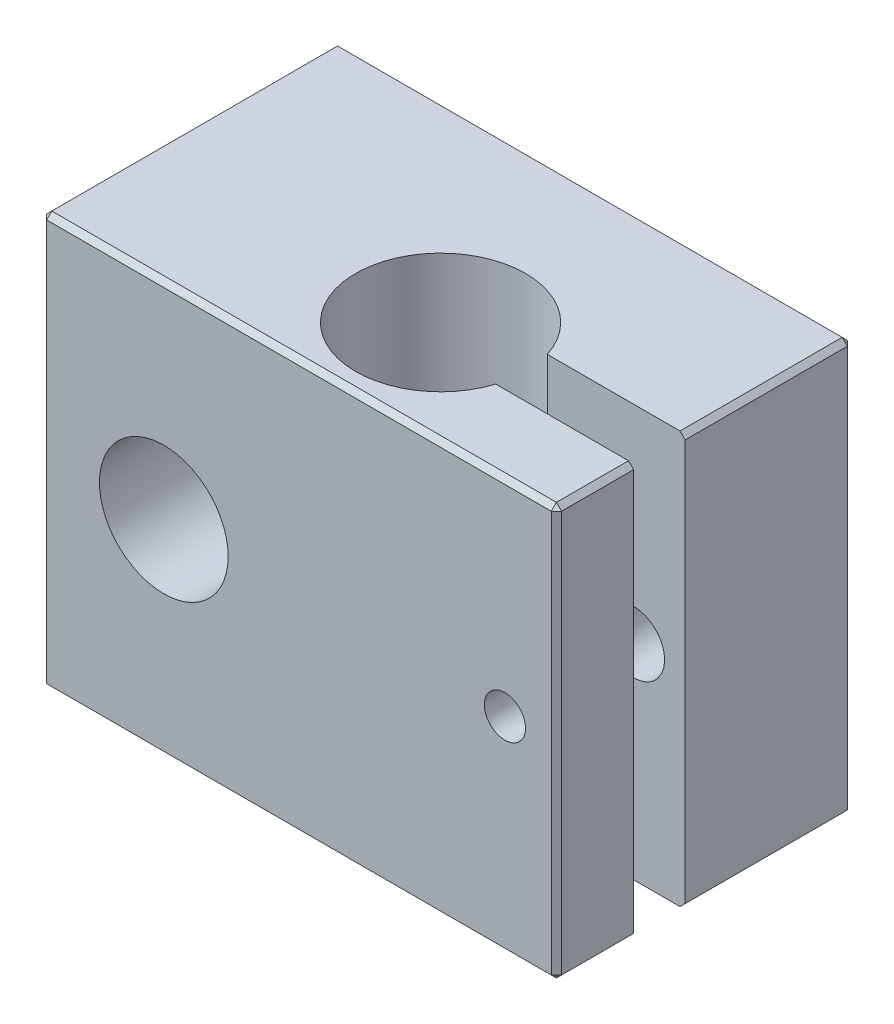
SolidWorks part; units mm, degrees
material "6061-O (SS)"
ref_plane "Plan de face" through (0, 0, 0) normal (0, 0, 1) x (1, 0, 0)
ref_plane "Plan de dessus" through (0, 0, 0) normal (0, 1, 0) x (1, 0, 0)
ref_plane "Plan de droite" through (0, 0, 0) normal (1, 0, 0) x (0, 0, -1)
sketch "Esquisse1" plane through (0, 0, 0) normal (0, 0, 1) x (1, 0, 0)
  line L1 (-4.75, 8) -> (15.25, 8)
  line L2 (-4.75, 8) -> (-4.75, -8)
  line L3 (-4.75, -8) -> (15.25, -8)
  line L4 (15.25, 8) -> (15.25, -8)
  dimension "D1" = 8
  dimension "D2" = 16
  dimension "D3" = 20
  dimension "D4" = 4.75
extrude "Boss.-Extru.1" add sketch "Esquisse1" along normal blind 11.5
hole_wizard "Trou taraudé M61" positions "Esquisse3" profile "Esquisse2" tap size "M6" standard "Iso" end condition through all
sketch "Esquisse3" plane through (0, 0, 11.5) normal (0, 0, 1) x (1, 0, 0)
  point P0 (0, 0)
sketch "Esquisse2" plane through (0, 0, 11.5) normal (1, 0, 0) x (0, -1, 0)
  line L0 (0, 0) -> (0, 11.5)
  line L1 (0, 11.5) -> (2.5, 11.5)
  line L2 (2.5, 11.5) -> (2.5, 0)
  line L5 (2.5, 0) -> (0, 0)
  line L11 (0, -6.35) -> (0, 107.95) construction
  dimension "Diamètre du trou pour taraudage jusqu'au prochain" = 5
  dimension "Profondeur du trou pour taraudage jusqu'au prochain" = 11.5
cosmetic thread "Filetage de perçage1" parameters "D2"=6
hole_wizard "Perçage1" positions "Esquisse5" profile "Esquisse4" legacy
sketch "Esquisse5" plane through (0, -8, 0) normal (0, -1, 0) x (-1, 0, 0)
  line L0 (4.75, -11.5) -> (4.75, 0) construction
  line L1 (4.75, -11.5) -> (-15.25, -11.5) construction
  point P0 (2.25, -9)
  dimension "D1" = 2.5
  dimension "D2" = 2.5
sketch "Esquisse4" plane through (-2.25, -8, 9) normal (1, 0, 0) x (0, 0, -1)
  line L0 (0, 0) -> (0, 4.5)
  line L1 (0, 4.5) -> (0.5, 4.5)
  line L2 (0.5, 4.5) -> (0.5, 2)
  line L3 (0.5, 2) -> (1, 2)
  line L4 (1, 2) -> (1, 0)
  line L5 (1, 0) -> (0, 0)
  line L6 (0, 110) -> (0, -10) construction
  dimension "Diamètre" = 1
  dimension "Profondeur" = 4.5
  dimension "Diamètre chambrage" = 2
  dimension "Profondeur chambrage" = 2
hole_wizard "Trou taraudé M2.51" positions "Esquisse7" profile "Esquisse6" tap size "M2.5" standard "Iso"
sketch "Esquisse7" plane through (0, -8, 0) normal (0, -1, 0) x (-1, 0, 0)
  line L0 (4.75, -11.5) -> (4.75, 0) construction
  line L1 (4.75, -11.5) -> (-15.25, -11.5) construction
  point P0 (1.25, -6.5)
  dimension "D1" = 3.5
  dimension "D2" = 5
sketch "Esquisse6" plane through (-1.25, -8, 6.5) normal (1, 0, 0) x (0, 0, -1)
  line L0 (0, 0) -> (0, 5.1159)
  line L1 (0, 5.1159) -> (1.025, 4.5)
  line L2 (1.025, 4.5) -> (1.025, 0)
  line L5 (1.025, 0) -> (0, 0)
  line L10 (0, 5.1159) -> (-1.025, 4.5) construction
  line L11 (0, -6.35) -> (0, 107.95) construction
  dimension "Diamètre du trou pour taraudage" = 2.05
  dimension "Profondeur du trou pour taraudage" = 4.5
  dimension "Angle de pointe" = 118
cosmetic thread "Filetage de perçage2" parameters "D1"=4, "D2"=3
hole_wizard "Dégagement M61" positions "Esquisse9" profile "Esquisse8" hole size "M6" standard "Ansi Metric" end condition through all
sketch "Esquisse9" plane through (0, -8, 0) normal (0, -1, 0) x (-1, 0, 0)
  line L0 (4.75, -11.5) -> (4.75, 0) construction
  line L1 (4.75, -11.5) -> (-15.25, -11.5) construction
  point P0 (-6.75, -7.5)
  dimension "D1" = 11.5
  dimension "D2" = 4
sketch "Esquisse8" plane through (6.75, -8, 7.5) normal (1, 0, 0) x (0, 0, -1)
  line L0 (0, 0) -> (0, 16)
  line L1 (0, 16) -> (3.3, 16)
  line L2 (3.3, 16) -> (3.3, 0)
  line L5 (3.3, 0) -> (0, 0)
  line L11 (0, -6.35) -> (0, 107.95) construction
  dimension "Diamètre du perçage jusqu'au prochain" = 6.6
  dimension "Profondeur du perçage jusqu'au prochain" = 16
sketch "Esquisse10" plane through (0, -8, 0) normal (0, -1, 0) x (1, 0, 0)
  line L0 (3.45, 7.5) -> (22.5625, 7.5) construction
  line L2 (6.75, 8.5) -> (18.2372, 8.5)
  line L3 (6.75, 8.5) -> (6.75, 6.5)
  line L4 (6.75, 6.5) -> (18.2372, 6.5)
  line L5 (18.2372, 8.5) -> (18.2372, 6.5)
  dimension "D1" = 1
  dimension "D2" = 1
extrude "Enlèv. mat.-Extru.1" cut sketch "Esquisse10" against normal through all
hole_wizard "Trou taraudé M21" positions "Esquisse12" profile "Esquisse11" tap size "M2" standard "Iso"
sketch "Esquisse12" plane through (0, 0, 11.5) normal (0, 0, 1) x (1, 0, 0)
  line L1 (15.25, -8) -> (15.25, 8) construction
  point P0 (13.25, 0)
  dimension "D1" = 2
sketch "Esquisse11" plane through (13.25, 0, 11.5) normal (1, 0, 0) x (0, -1, 0)
  line L0 (0, 0) -> (0, 3)
  line L1 (0, 3) -> (0.8, 3)
  line L2 (0.8, 3) -> (0.8, 0)
  line L5 (0.8, 0) -> (0, 0)
  line L11 (0, -6.35) -> (0, 107.95) construction
  dimension "Diamètre du trou pour taraudage jusqu'au prochain" = 1.6
  dimension "Profondeur du trou pour taraudage jusqu'au prochain" = 3
cosmetic thread "Filetage de perçage3" parameters "D2"=2
hole_wizard "Dégagement M21" positions "Esquisse16" profile "Esquisse15" hole size "M2" standard "Ansi Metric"
sketch "Esquisse16" plane through (0, 0, 0) normal (0, 0, -1) x (-1, 0, 0)
  line L0 (-15.25, -8) -> (-15.25, 8) construction
  point P0 (-13.25, 0)
  dimension "D1" = 2
sketch "Esquisse15" plane through (13.25, 0, 0) normal (1, 0, 0) x (0, 1, 0)
  line L0 (0, 0) -> (0, 6.5)
  line L1 (0, 6.5) -> (1.2, 6.5)
  line L2 (1.2, 6.5) -> (1.2, 0)
  line L5 (1.2, 0) -> (0, 0)
  line L11 (0, -6.35) -> (0, 107.95) construction
  dimension "Diamètre du perçage jusqu'au prochain" = 2.4
  dimension "Profondeur du perçage jusqu'au prochain" = 6.5
chamfer "Chanfrein1" distance 0.2 angle 45 14 edges at (5.25, -8, 0) (-4.75, -8, 5.75) (-4.75, 0, 0) (15.25, -8, 3.25) (15.25, 0, 0) (15.25, 8, 3.25) (5.25, 8, 0) (-4.75, 8, 5.75) (15.25, -8, 10) (15.25, 8, 10) (5.25, -8, 11.5) (15.25, 0, 11.5) (5.25, 8, 11.5) (-4.75, 0, 11.5)
equation "\"D2@Esquisse5\"=\"D1@Esquisse5\""
equation "\"D2@Esquisse10\"=\"D1@Esquisse10\""
